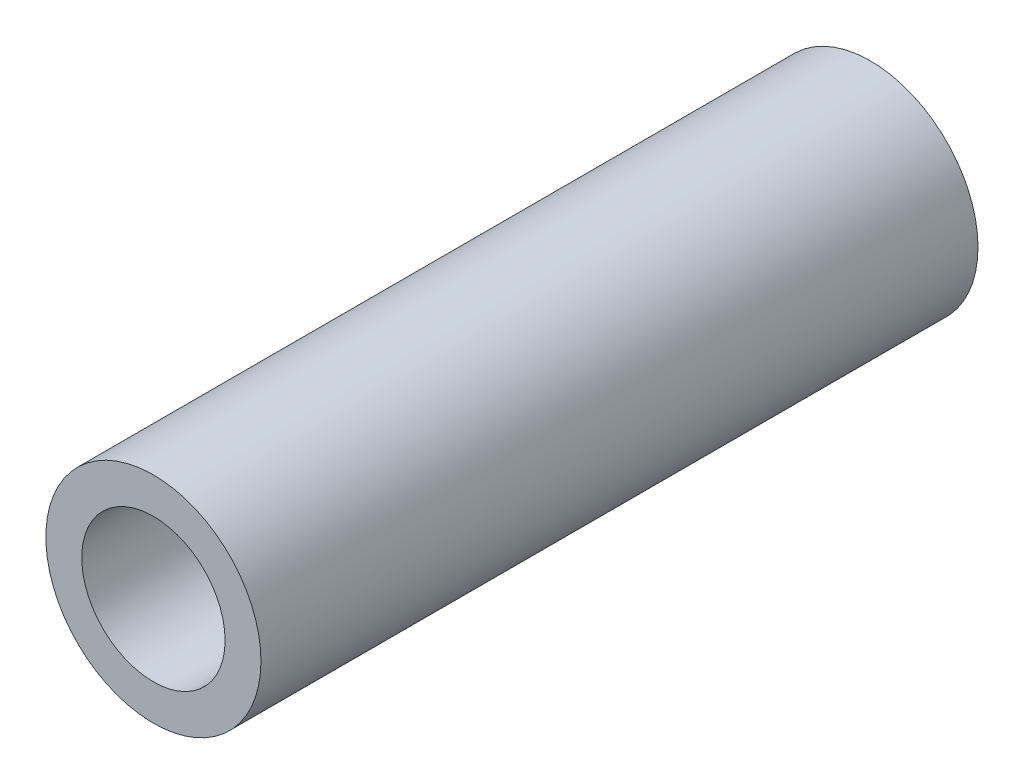
SolidWorks part; units mm, degrees
material "Ст 3 ГОСТ 380-88"
ref_plane "Спереди" through (0, 0, 0) normal (0, 0, 1) x (1, 0, 0)
ref_plane "Сверху" through (0, 0, 0) normal (0, 1, 0) x (1, 0, 0)
ref_plane "Справа" through (0, 0, 0) normal (1, 0, 0) x (0, 0, -1)
sketch "Эскиз1" plane through (0, 0, 0) normal (0, 0, 1) x (1, 0, 0)
  circle A0 centre (0, 0) radius 9
  dimension "D1" = 18
extrude "Вытянуть-Тонкостенный1" add sketch "Эскиз1" along normal blind 30 and the other way blind 30 thin contours A0 thin type one direction reverse wall 3
